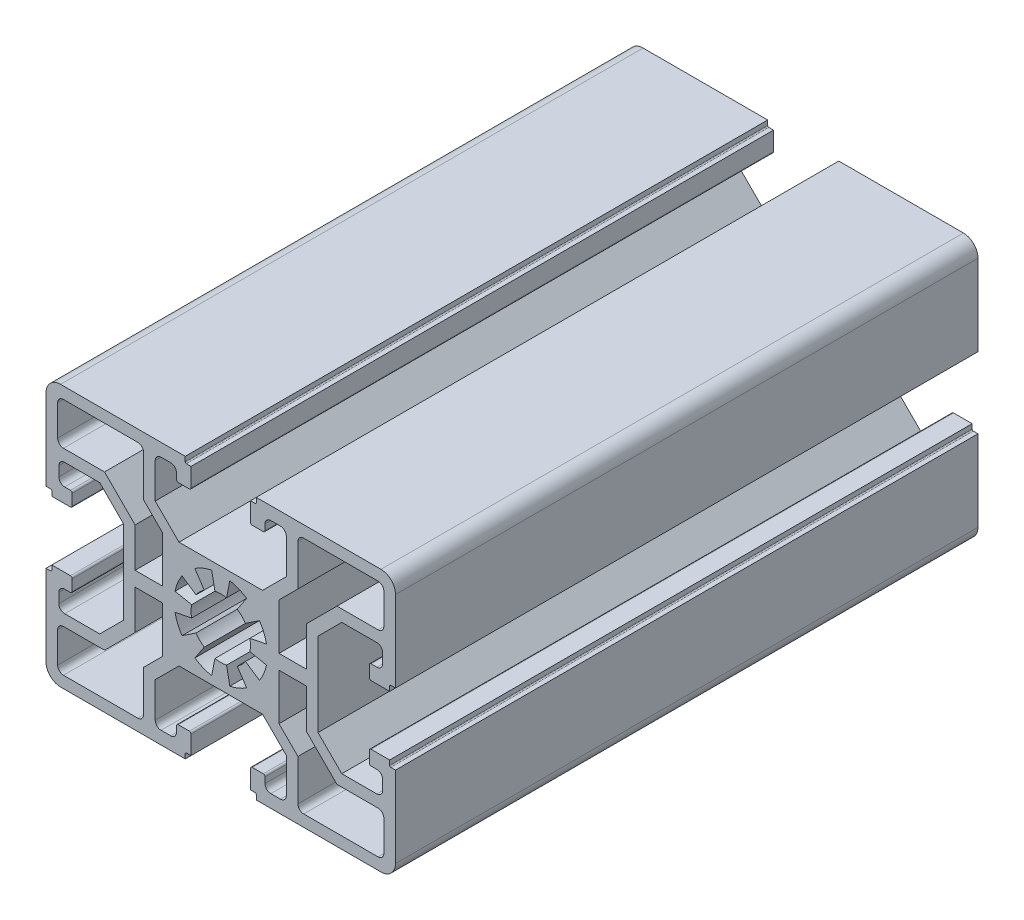
SolidWorks part; units mm, degrees
ref_plane "前视基准面" through (0, 0, 0) normal (0, 0, 1) x (1, 0, 0)
ref_plane "上视基准面" through (0, 0, 0) normal (0, 1, 0) x (1, 0, 0)
ref_plane "右视基准面" through (0, 0, 0) normal (1, 0, 0) x (0, 0, -1)
sketch "草图1" plane through (0, 0, 0) normal (0, 0, 1) x (1, 0, 0)
  line L0 (-5.6744, 22.6514) -> (-27.0744, 22.6514)
  line L1 (-29.5744, 20.1514) -> (-29.5744, 6.2514)
  line L2 (-4.6744, 21.6514) -> (-4.6744, 18.4514)
  line L3 (-4.9744, 18.1514) -> (-6.8744, 18.1514)
  line L4 (-7.1744, 18.4514) -> (-7.1744, 19.4514)
  line L5 (-8.1744, 20.4514) -> (-9.8244, 20.4514)
  line L6 (-10.8244, 19.4514) -> (-10.8244, 13.4298)
  line L7 (-20.3528, 11.4014) -> (-26.3744, 11.4014)
  line L8 (-27.3744, 10.4014) -> (-27.3744, 8.7514)
  line L9 (-26.3744, 7.7514) -> (-25.3744, 7.7514)
  line L10 (-25.0744, 7.4514) -> (-25.0744, 5.5514)
  line L11 (-25.3744, 5.2514) -> (-28.5744, 5.2514)
  line L12 (-4.6744, 21.6514) -> (-5.4744, 21.6514)
  line L13 (-5.6744, 21.8514) -> (-5.6744, 22.6514)
  line L14 (-29.5744, 6.2514) -> (-28.7744, 6.2514)
  line L15 (-28.5744, 6.0514) -> (-28.5744, 5.2514)
  line L16 (-14.2744, 8.1514) -> (-14.2744, 1.4014)
  line L17 (7.0774, 4.596) -> (4.6661, 2.9848)
  line L18 (1.9863, -7.6949) -> (1.4206, -4.8506)
  line L19 (-4.019, -6.5004) -> (-2.4078, -4.0891)
  line L20 (-1.1351, -7.6949) -> (-0.5694, -4.8506)
  line L21 (4.8702, -6.5004) -> (3.259, -4.0891)
  line L22 (7.0774, -4.2932) -> (4.6661, -2.682)
  line L23 (8.2719, -1.4093) -> (5.4276, -0.8436)
  line L24 (8.2719, 1.7121) -> (5.4276, 1.1464)
  line L25 (4.8702, 6.8032) -> (3.259, 4.3919)
  line L26 (-7.4207, 1.7121) -> (-4.5764, 1.1464)
  line L27 (1.9863, 7.9977) -> (1.4206, 5.1534)
  line L28 (-1.1351, 7.9977) -> (-0.5694, 5.1534)
  line L29 (-4.019, 6.8032) -> (-2.4078, 4.3919)
  line L30 (-6.2261, 4.596) -> (-3.8149, 2.9848)
  line L31 (-7.4207, -1.4093) -> (-4.5764, -0.8436)
  line L32 (-12.8244, 12.6014) -> (-12.8244, 19.6514)
  line L33 (-13.8244, 20.6514) -> (-26.5744, 20.6514)
  line L34 (-27.5744, 19.6514) -> (-27.5744, 14.4014)
  line L35 (-26.5744, 13.4014) -> (-19.5244, 13.4014)
  line L36 (-6.2261, -4.2932) -> (-3.8149, -2.682)
  line L37 (-9.5744, 9.3514) -> (-9.5744, 1.4014)
  line L38 (-14.2744, 1.4014) -> (-9.5744, 1.4014)
  line L39 (-9.5744, 9.3514) -> (-12.8244, 12.6014)
  line L40 (-6.746, 9.3514) -> (-10.8244, 13.4298)
  line L41 (-16.2744, 7.323) -> (-20.3528, 11.4014)
  line L42 (-14.2744, 8.1514) -> (-19.5244, 13.4014)
  line L43 (6.5256, 22.6514) -> (27.9256, 22.6514)
  line L44 (30.4256, 20.1514) -> (30.4256, 6.2514)
  line L45 (5.5256, 21.6514) -> (5.5256, 18.4514)
  line L46 (5.8256, 18.1514) -> (7.7256, 18.1514)
  line L47 (8.0256, 18.4514) -> (8.0256, 19.4514)
  line L48 (9.0256, 20.4514) -> (10.6756, 20.4514)
  line L49 (11.6756, 19.4514) -> (11.6756, 13.4298)
  line L50 (21.204, 11.4014) -> (27.2256, 11.4014)
  line L51 (28.2256, 10.4014) -> (28.2256, 8.7514)
  line L52 (27.2256, 7.7514) -> (26.2256, 7.7514)
  line L53 (25.9256, 7.4514) -> (25.9256, 5.5514)
  line L54 (26.2256, 5.2514) -> (29.4256, 5.2514)
  line L55 (5.5256, 21.6514) -> (6.3256, 21.6514)
  line L56 (6.5256, 21.8514) -> (6.5256, 22.6514)
  line L57 (30.4256, 6.2514) -> (29.6256, 6.2514)
  line L58 (29.4256, 6.0514) -> (29.4256, 5.2514)
  line L59 (15.1256, 8.1514) -> (15.1256, 1.4014)
  line L60 (13.6756, 12.6014) -> (13.6756, 19.6514)
  line L61 (14.6756, 20.6514) -> (27.4256, 20.6514)
  line L62 (28.4256, 19.6514) -> (28.4256, 14.4014)
  line L63 (27.4256, 13.4014) -> (20.3756, 13.4014)
  line L64 (10.4256, 9.3514) -> (10.4256, 1.4014)
  line L65 (15.1256, 1.4014) -> (10.4256, 1.4014)
  line L66 (10.4256, 9.3514) -> (13.6756, 12.6014)
  line L67 (17.1256, 7.323) -> (21.204, 11.4014)
  line L68 (15.1256, 8.1514) -> (20.3756, 13.4014)
  line L69 (7.5972, 9.3514) -> (11.6756, 13.4298)
  line L70 (7.5972, 9.3514) -> (-6.746, 9.3514)
  line L71 (-16.2744, 7.323) -> (-16.2744, 0.1514)
  line L72 (17.1256, 7.323) -> (17.1256, 0.1514)
  line L73 (-5.6744, -22.3486) -> (-27.0744, -22.3486)
  line L74 (-29.5744, -19.8486) -> (-29.5744, -5.9486)
  line L75 (-4.6744, -21.3486) -> (-4.6744, -18.1486)
  line L76 (-4.9744, -17.8486) -> (-6.8744, -17.8486)
  line L77 (-7.1744, -18.1486) -> (-7.1744, -19.1486)
  line L78 (-8.1744, -20.1486) -> (-9.8244, -20.1486)
  line L79 (-10.8244, -19.1486) -> (-10.8244, -13.127)
  line L80 (-20.3528, -11.0986) -> (-26.3744, -11.0986)
  line L81 (-27.3744, -10.0986) -> (-27.3744, -8.4486)
  line L82 (-26.3744, -7.4486) -> (-25.3744, -7.4486)
  line L83 (-25.0744, -7.1486) -> (-25.0744, -5.2486)
  line L84 (-25.3744, -4.9486) -> (-28.5744, -4.9486)
  line L85 (-4.6744, -21.3486) -> (-5.4744, -21.3486)
  line L86 (-5.6744, -21.5486) -> (-5.6744, -22.3486)
  line L87 (-29.5744, -5.9486) -> (-28.7744, -5.9486)
  line L88 (-28.5744, -5.7486) -> (-28.5744, -4.9486)
  line L89 (7.5972, -9.0486) -> (-6.746, -9.0486)
  line L90 (-14.2744, -7.8486) -> (-14.2744, -1.0986)
  line L91 (-12.8244, -12.2986) -> (-12.8244, -19.3486)
  line L92 (-13.8244, -20.3486) -> (-26.5744, -20.3486)
  line L93 (-27.5744, -19.3486) -> (-27.5744, -14.0986)
  line L94 (-26.5744, -13.0986) -> (-19.5244, -13.0986)
  line L95 (-9.5744, -9.0486) -> (-9.5744, -1.0986)
  line L96 (-14.2744, -1.0986) -> (-9.5744, -1.0986)
  line L97 (-9.5744, -9.0486) -> (-12.8244, -12.2986)
  line L98 (-6.746, -9.0486) -> (-10.8244, -13.127)
  line L99 (-16.2744, -7.0202) -> (-20.3528, -11.0986)
  line L100 (-14.2744, -7.8486) -> (-19.5244, -13.0986)
  line L101 (6.5256, -22.3486) -> (27.9256, -22.3486)
  line L102 (30.4256, -19.8486) -> (30.4256, -5.9486)
  line L103 (5.5256, -21.3486) -> (5.5256, -18.1486)
  line L104 (5.8256, -17.8486) -> (7.7256, -17.8486)
  line L105 (8.0256, -18.1486) -> (8.0256, -19.1486)
  line L106 (9.0256, -20.1486) -> (10.6756, -20.1486)
  line L107 (11.6756, -19.1486) -> (11.6756, -13.127)
  line L108 (21.204, -11.0986) -> (27.2256, -11.0986)
  line L109 (28.2256, -10.0986) -> (28.2256, -8.4486)
  line L110 (27.2256, -7.4486) -> (26.2256, -7.4486)
  line L111 (25.9256, -7.1486) -> (25.9256, -5.2486)
  line L112 (26.2256, -4.9486) -> (29.4256, -4.9486)
  line L113 (5.5256, -21.3486) -> (6.3256, -21.3486)
  line L114 (6.5256, -21.5486) -> (6.5256, -22.3486)
  line L115 (30.4256, -5.9486) -> (29.6256, -5.9486)
  line L116 (29.4256, -5.7486) -> (29.4256, -4.9486)
  line L117 (15.1256, -7.8486) -> (15.1256, -1.0986)
  line L118 (13.6756, -12.2986) -> (13.6756, -19.3486)
  line L119 (14.6756, -20.3486) -> (27.4256, -20.3486)
  line L120 (28.4256, -19.3486) -> (28.4256, -14.0986)
  line L121 (27.4256, -13.0986) -> (20.3756, -13.0986)
  line L122 (10.4256, -9.0486) -> (10.4256, -1.0986)
  line L123 (15.1256, -1.0986) -> (10.4256, -1.0986)
  line L124 (10.4256, -9.0486) -> (13.6756, -12.2986)
  line L125 (17.1256, -7.0202) -> (21.204, -11.0986)
  line L126 (15.1256, -7.8486) -> (20.3756, -13.0986)
  line L127 (7.5972, -9.0486) -> (11.6756, -13.127)
  line L128 (-16.2744, -7.0202) -> (-16.2744, 0.1514)
  line L129 (17.1256, -7.0202) -> (17.1256, 0.1514)
  arc A0 (-27.0744, 22.6514) -> (-29.5744, 20.1514) centre (-27.0744, 20.1514) ccw
  arc A1 (-4.9744, 18.1514) -> (-4.6744, 18.4514) centre (-4.9744, 18.4514) ccw
  arc A2 (-7.1744, 18.4514) -> (-6.8744, 18.1514) centre (-6.8744, 18.4514) ccw
  arc A3 (-7.1744, 19.4514) -> (-8.1744, 20.4514) centre (-8.1744, 19.4514) ccw
  arc A4 (-9.8244, 20.4514) -> (-10.8244, 19.4514) centre (-9.8244, 19.4514) ccw
  arc A5 (-26.3744, 11.4014) -> (-27.3744, 10.4014) centre (-26.3744, 10.4014) ccw
  arc A6 (-27.3744, 8.7514) -> (-26.3744, 7.7514) centre (-26.3744, 8.7514) ccw
  arc A7 (-25.0744, 7.4514) -> (-25.3744, 7.7514) centre (-25.3744, 7.4514) ccw
  arc A8 (-25.3744, 5.2514) -> (-25.0744, 5.5514) centre (-25.3744, 5.5514) ccw
  arc A9 (-5.6744, 21.8514) -> (-5.4744, 21.6514) centre (-5.4744, 21.8514) ccw
  arc A10 (-28.5744, 6.0514) -> (-28.7744, 6.2514) centre (-28.7744, 6.0514) ccw
  arc A11 (-1.1351, 7.9977) -> (-4.019, 6.8032) centre (0.4256, 0.1514) ccw
  arc A12 (-6.2261, 4.596) -> (-7.4207, 1.7121) centre (0.4256, 0.1514) ccw
  arc A13 (-0.5694, -4.8506) -> (1.4206, -4.8506) centre (0.4256, 0.1514) ccw
  arc A14 (3.259, -4.0891) -> (4.6661, -2.682) centre (0.4256, 0.1514) ccw
  arc A15 (5.4276, -0.8436) -> (5.4276, 1.1464) centre (0.4256, 0.1514) ccw
  arc A16 (4.6661, 2.9848) -> (3.259, 4.3919) centre (0.4256, 0.1514) ccw
  arc A17 (1.4206, 5.1534) -> (-0.5694, 5.1534) centre (0.4256, 0.1514) ccw
  arc A18 (-2.4078, 4.3919) -> (-3.8149, 2.9848) centre (0.4256, 0.1514) ccw
  arc A19 (-4.5764, 1.1464) -> (-4.5764, -0.8436) centre (0.4256, 0.1514) ccw
  arc A20 (-3.8149, -2.682) -> (-2.4078, -4.0891) centre (0.4256, 0.1514) ccw
  arc A21 (-4.019, -6.5004) -> (-1.1351, -7.6949) centre (0.4256, 0.1514) ccw
  arc A22 (1.9863, -7.6949) -> (4.8702, -6.5004) centre (0.4256, 0.1514) ccw
  arc A23 (7.0774, -4.2932) -> (8.2719, -1.4093) centre (0.4256, 0.1514) ccw
  arc A24 (8.2719, 1.7121) -> (7.0774, 4.596) centre (0.4256, 0.1514) ccw
  arc A25 (4.8702, 6.8032) -> (1.9863, 7.9977) centre (0.4256, 0.1514) ccw
  arc A26 (-7.4207, -1.4093) -> (-6.2261, -4.2932) centre (0.4256, 0.1514) ccw
  arc A27 (-12.8244, 19.6514) -> (-13.8244, 20.6514) centre (-13.8244, 19.6514) ccw
  arc A28 (-26.5744, 20.6514) -> (-27.5744, 19.6514) centre (-26.5744, 19.6514) ccw
  arc A29 (-27.5744, 14.4014) -> (-26.5744, 13.4014) centre (-26.5744, 14.4014) ccw
  arc A30 (30.4256, 20.1514) -> (27.9256, 22.6514) centre (27.9256, 20.1514) ccw
  arc A31 (5.5256, 18.4514) -> (5.8256, 18.1514) centre (5.8256, 18.4514) ccw
  arc A32 (7.7256, 18.1514) -> (8.0256, 18.4514) centre (7.7256, 18.4514) ccw
  arc A33 (9.0256, 20.4514) -> (8.0256, 19.4514) centre (9.0256, 19.4514) ccw
  arc A34 (11.6756, 19.4514) -> (10.6756, 20.4514) centre (10.6756, 19.4514) ccw
  arc A35 (28.2256, 10.4014) -> (27.2256, 11.4014) centre (27.2256, 10.4014) ccw
  arc A36 (27.2256, 7.7514) -> (28.2256, 8.7514) centre (27.2256, 8.7514) ccw
  arc A37 (26.2256, 7.7514) -> (25.9256, 7.4514) centre (26.2256, 7.4514) ccw
  arc A38 (25.9256, 5.5514) -> (26.2256, 5.2514) centre (26.2256, 5.5514) ccw
  arc A39 (6.3256, 21.6514) -> (6.5256, 21.8514) centre (6.3256, 21.8514) ccw
  arc A40 (29.6256, 6.2514) -> (29.4256, 6.0514) centre (29.6256, 6.0514) ccw
  arc A41 (14.6756, 20.6514) -> (13.6756, 19.6514) centre (14.6756, 19.6514) ccw
  arc A42 (28.4256, 19.6514) -> (27.4256, 20.6514) centre (27.4256, 19.6514) ccw
  arc A43 (27.4256, 13.4014) -> (28.4256, 14.4014) centre (27.4256, 14.4014) ccw
  arc A44 (-29.5744, -19.8486) -> (-27.0744, -22.3486) centre (-27.0744, -19.8486) ccw
  arc A45 (-4.6744, -18.1486) -> (-4.9744, -17.8486) centre (-4.9744, -18.1486) ccw
  arc A46 (-6.8744, -17.8486) -> (-7.1744, -18.1486) centre (-6.8744, -18.1486) ccw
  arc A47 (-8.1744, -20.1486) -> (-7.1744, -19.1486) centre (-8.1744, -19.1486) ccw
  arc A48 (-10.8244, -19.1486) -> (-9.8244, -20.1486) centre (-9.8244, -19.1486) ccw
  arc A49 (-27.3744, -10.0986) -> (-26.3744, -11.0986) centre (-26.3744, -10.0986) ccw
  arc A50 (-26.3744, -7.4486) -> (-27.3744, -8.4486) centre (-26.3744, -8.4486) ccw
  arc A51 (-25.3744, -7.4486) -> (-25.0744, -7.1486) centre (-25.3744, -7.1486) ccw
  arc A52 (-25.0744, -5.2486) -> (-25.3744, -4.9486) centre (-25.3744, -5.2486) ccw
  arc A53 (-5.4744, -21.3486) -> (-5.6744, -21.5486) centre (-5.4744, -21.5486) ccw
  arc A54 (-28.7744, -5.9486) -> (-28.5744, -5.7486) centre (-28.7744, -5.7486) ccw
  arc A55 (-13.8244, -20.3486) -> (-12.8244, -19.3486) centre (-13.8244, -19.3486) ccw
  arc A56 (-27.5744, -19.3486) -> (-26.5744, -20.3486) centre (-26.5744, -19.3486) ccw
  arc A57 (-26.5744, -13.0986) -> (-27.5744, -14.0986) centre (-26.5744, -14.0986) ccw
  arc A58 (27.9256, -22.3486) -> (30.4256, -19.8486) centre (27.9256, -19.8486) ccw
  arc A59 (5.8256, -17.8486) -> (5.5256, -18.1486) centre (5.8256, -18.1486) ccw
  arc A60 (8.0256, -18.1486) -> (7.7256, -17.8486) centre (7.7256, -18.1486) ccw
  arc A61 (8.0256, -19.1486) -> (9.0256, -20.1486) centre (9.0256, -19.1486) ccw
  arc A62 (10.6756, -20.1486) -> (11.6756, -19.1486) centre (10.6756, -19.1486) ccw
  arc A63 (27.2256, -11.0986) -> (28.2256, -10.0986) centre (27.2256, -10.0986) ccw
  arc A64 (28.2256, -8.4486) -> (27.2256, -7.4486) centre (27.2256, -8.4486) ccw
  arc A65 (25.9256, -7.1486) -> (26.2256, -7.4486) centre (26.2256, -7.1486) ccw
  arc A66 (26.2256, -4.9486) -> (25.9256, -5.2486) centre (26.2256, -5.2486) ccw
  arc A67 (6.5256, -21.5486) -> (6.3256, -21.3486) centre (6.3256, -21.5486) ccw
  arc A68 (29.4256, -5.7486) -> (29.6256, -5.9486) centre (29.6256, -5.7486) ccw
  arc A69 (13.6756, -19.3486) -> (14.6756, -20.3486) centre (14.6756, -19.3486) ccw
  arc A70 (27.4256, -20.3486) -> (28.4256, -19.3486) centre (27.4256, -19.3486) ccw
  arc A71 (28.4256, -14.0986) -> (27.4256, -13.0986) centre (27.4256, -14.0986) ccw
extrude "凸台-拉伸1" add sketch "草图1" along normal blind 100
